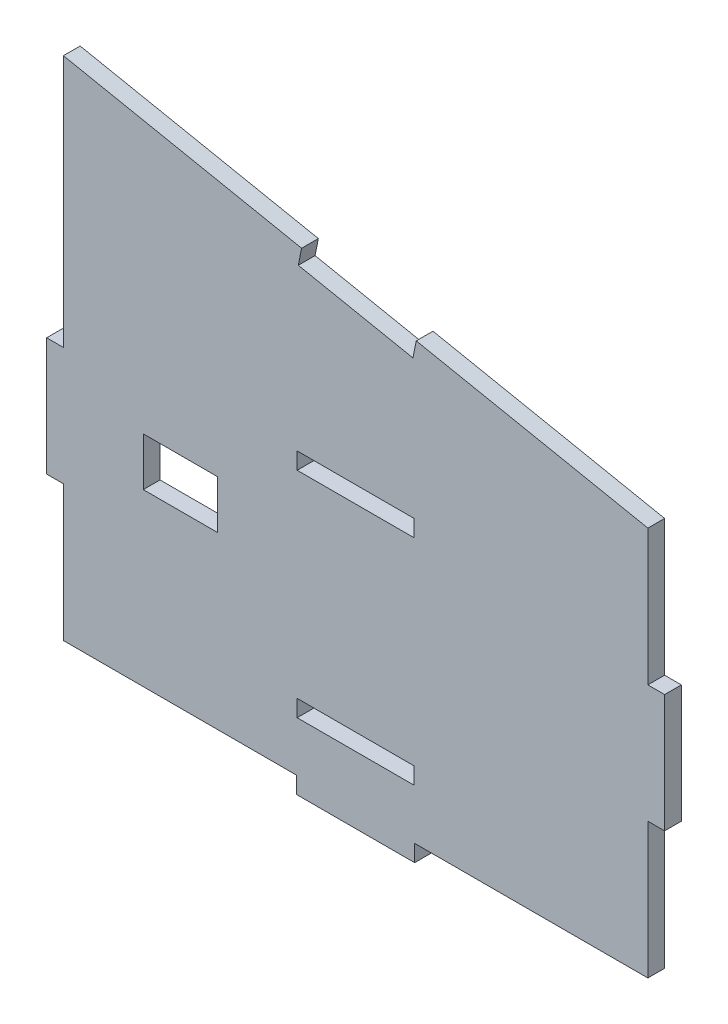
SolidWorks part; units mm, degrees
ref_plane "Front Plane" through (0, 0, 0) normal (0, 0, 1) x (1, 0, 0)
ref_plane "Top Plane" through (0, 0, 0) normal (0, 1, 0) x (1, 0, 0)
ref_plane "Right Plane" through (0, 0, 0) normal (1, 0, 0) x (0, 0, -1)
sketch "Sketch1" plane through (0, 0, 0) normal (0, 0, 1) x (1, 0, 0)
  line L0 (0, 130) -> (0, 65.15)
  line L1 (0, 0) -> (59.85, 0)
  line L2 (150, 0) -> (150, 34.85)
  line L3 (150, 100) -> (90.552, 111.8896)
  line L5 (0, 65.15) -> (-4.3, 65.15)
  line L7 (0, 34.85) -> (-4.3, 34.85)
  line L8 (-4.3, 65.15) -> (-4.3, 34.85)
  line L9 (150, 65.15) -> (154.3, 65.15)
  line L11 (150, 34.85) -> (154.3, 34.85)
  line L12 (154.3, 65.15) -> (154.3, 34.85)
  line L14 (90.15, 0) -> (90.15, -4.3)
  line L15 (90.15, -4.3) -> (59.85, -4.3)
  line L16 (59.85, 0) -> (59.85, -4.3)
  line L17 (90.552, 111.8896) -> (89.7087, 107.6731)
  line L18 (61.1346, 117.7731) -> (60.2913, 113.5566)
  line L19 (89.7087, 107.6731) -> (60.2913, 113.5566)
  line L20 (90.15, 0) -> (150, 0)
  line L21 (150, 65.15) -> (150, 100)
  line L22 (0, 34.85) -> (0, 0)
  line L23 (61.1346, 117.7731) -> (0, 130)
  line L25 (60, 17.15) -> (90, 17.15)
  line L26 (60, 17.15) -> (60, 12.85)
  line L27 (60, 12.85) -> (90, 12.85)
  line L28 (90, 17.15) -> (90, 12.85)
  line L29 (60, 17.15) -> (90, 12.85) construction
  line L30 (60, 12.85) -> (90, 17.15) construction
  line L31 (60, 72.15) -> (90, 72.15)
  line L32 (60, 72.15) -> (60, 67.85)
  line L33 (60, 67.85) -> (90, 67.85)
  line L34 (90, 72.15) -> (90, 67.85)
  line L35 (60, 72.15) -> (90, 67.85) construction
  line L36 (60, 67.85) -> (90, 72.15) construction
  line L37 (39.5, 43.8) -> (20.5, 43.8)
  line L38 (39.5, 43.8) -> (39.5, 56.2)
  line L39 (39.5, 56.2) -> (20.5, 56.2)
  line L40 (20.5, 43.8) -> (20.5, 56.2)
  line L41 (39.5, 43.8) -> (20.5, 56.2) construction
  line L42 (39.5, 56.2) -> (20.5, 43.8) construction
  point P17 (75, 110.6148)
  point P20 (75, -4.3)
  point P23 (-4.3, 50)
  point P24 (154.3, 50)
  point P25 (75, 15)
  point P30 (30, 50)
  point P31 (75, 70)
  dimension "D1" = 130
  dimension "D2" = 100
  dimension "D3" = 150
  dimension "D4" = 75
  dimension "D5" = 30.3
  dimension "D6" = 4.3
  dimension "D7" = 50
  dimension "D8" = 30
  dimension "D9" = 4.3
  dimension "D10" = 15
  dimension "D11" = 70
  dimension "D12" = 30
  dimension "D13" = 19
  dimension "D14" = 12.4
  dimension "D15" = 50
  dimension "D16" = 30
extrude "Boss-Extrude1" add sketch "Sketch1" along normal blind 4.3
